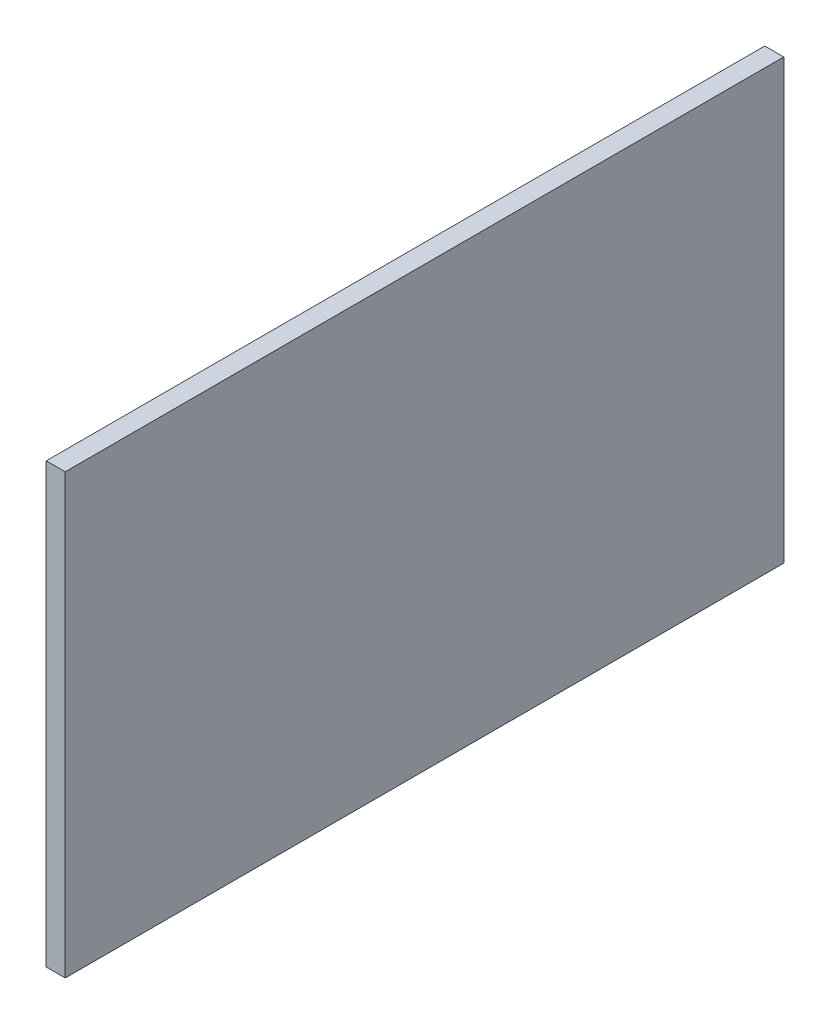
SolidWorks part; units mm, degrees
ref_plane "Front Plane" through (0, 0, 0) normal (0, 0, 1) x (1, 0, 0)
ref_plane "Top Plane" through (0, 0, 0) normal (0, 1, 0) x (1, 0, 0)
ref_plane "Right Plane" through (0, 0, 0) normal (1, 0, 0) x (0, 0, -1)
sketch "Sketch1" plane through (0, 0, 0) normal (1, 0, 0) x (0, 0, -1)
  line L1 (0, 0) -> (454, 0)
  line L2 (0, 0) -> (0, 277)
  line L3 (0, 277) -> (454, 277)
  line L4 (454, 0) -> (454, 277)
  dimension "D1" = 277
  dimension "D2" = 454
extrude "Boss-Extrude1" add sketch "Sketch1" along normal blind 12
